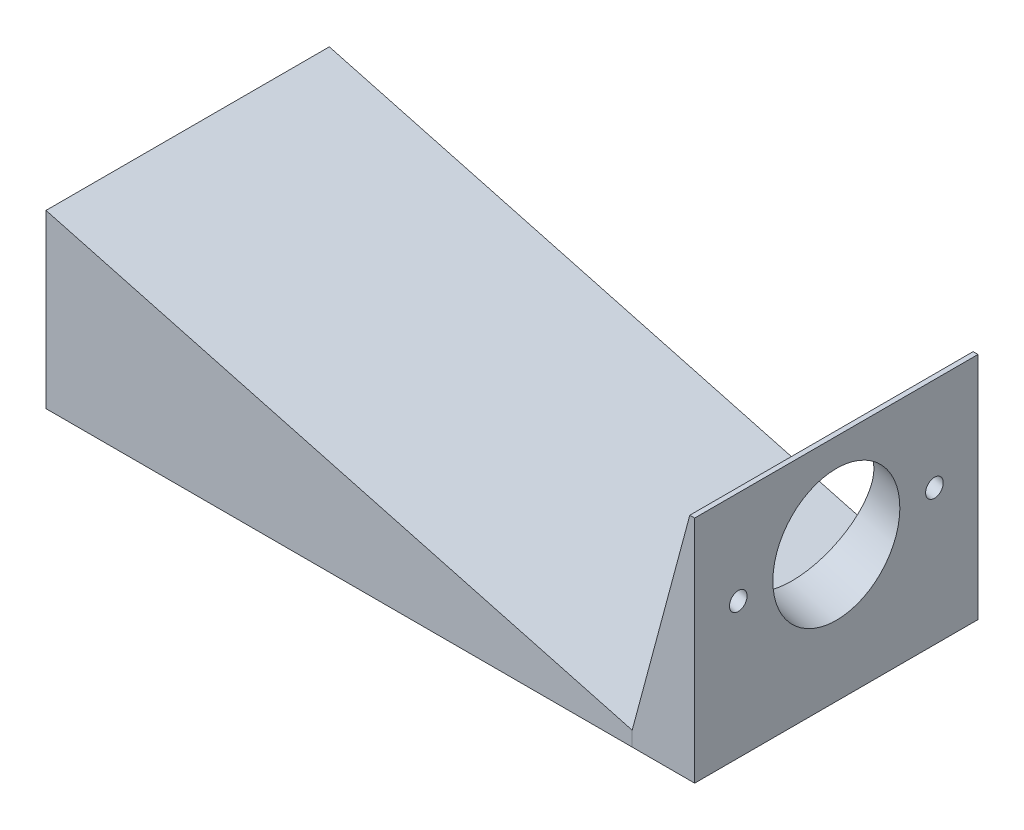
SolidWorks part; units mm, degrees
ref_plane "Alzado" through (0, 0, 0) normal (0, 0, 1) x (1, 0, 0)
ref_plane "Planta" through (0, 0, 0) normal (0, 1, 0) x (1, 0, 0)
ref_plane "Vista lateral" through (0, 0, 0) normal (1, 0, 0) x (0, 0, -1)
sketch "Croquis1" plane through (0, 0, 0) normal (0, 0, 1) x (1, 0, 0)
  line L0 (-30, 0) -> (30, 0)
  line L1 (-30, 0) -> (-30, 17.577)
  line L3 (-30, 17.577) -> (30, 1.5)
  line L4 (30, 1.5) -> (27.8666, 1.5) construction
  line L6 (30, 1.5) -> (-30, 1.5) construction
  line L11 (30, 1.5) -> (30, 0)
  point P4 (0, 0)
  dimension "D1" = 60
  dimension "D2" = 15
  dimension "D3" = 1.5
extrude "Saliente-Extruir1" add sketch "Croquis1" against normal blind 29
sketch "Croquis3" plane through (0, 0, 0) normal (0, 0, 1) x (1, 0, 0)
  line L0 (30, 0) -> (30, 1.5)
  line L1 (30, 1.5) -> (35.8962, 23.5048)
  line L2 (35.8962, 23.5048) -> (36.3962, 23.5048)
  line L3 (36.3962, 23.5048) -> (36.3962, 0)
  line L4 (36.3962, 0) -> (30, 0)
  line L5 (30, 1.5) -> (-30, 1.5) construction
  line L6 (-30, 17.577) -> (-30, 0) construction
  line L7 (30, 1.5) -> (36.3962, 1.5) construction
  dimension "D1" = 0.5
  dimension "D2" = 75
extrude "Saliente-Extruir2" add sketch "Croquis3" against normal blind 29 separate body
sketch "Croquis6" plane through (27.6154, -7.3995, 0) normal (-0.9659, 0.2588, 0) x (0, 0, 1)
  line L0 (-14.5, 9.2135) -> (-14.5, 31.9945) construction
  line L1 (-29, 9.2135) -> (0, 9.2135) construction
  line L2 (-29, 31.9945) -> (0, 31.9945) construction
  circle A0 centre (-14.5, 22.8635) radius 6.5
  dimension "D1" = 13
  dimension "D2" = 13.65
extrude "Cortar-Extruir1" cut sketch "Croquis6" against normal through all
sketch "Croquis9" plane through (27.6154, -7.3995, 0) normal (-0.9659, 0.2588, 0) x (0, 0, 1)
  line L0 (-14.5, 22.8635) -> (-24.54, 22.8635) construction
  line L3 (-14.5, 22.8635) -> (-14.5, 9.2135) construction
  line L4 (-29, 9.2135) -> (0, 9.2135) construction
  circle A0 centre (-14.5, 22.8635) radius 6.5 construction
  circle A1 centre (-14.5, 22.8635) radius 6.5
  circle A2 centre (-24.54, 22.8635) radius 0.9
  circle A3 centre (-4.46, 22.8635) radius 0.9
  dimension "D2" = 1.8
  dimension "D1" = 10.04
extrude "Cortar-Extruir2" cut sketch "Croquis9" against normal through all
